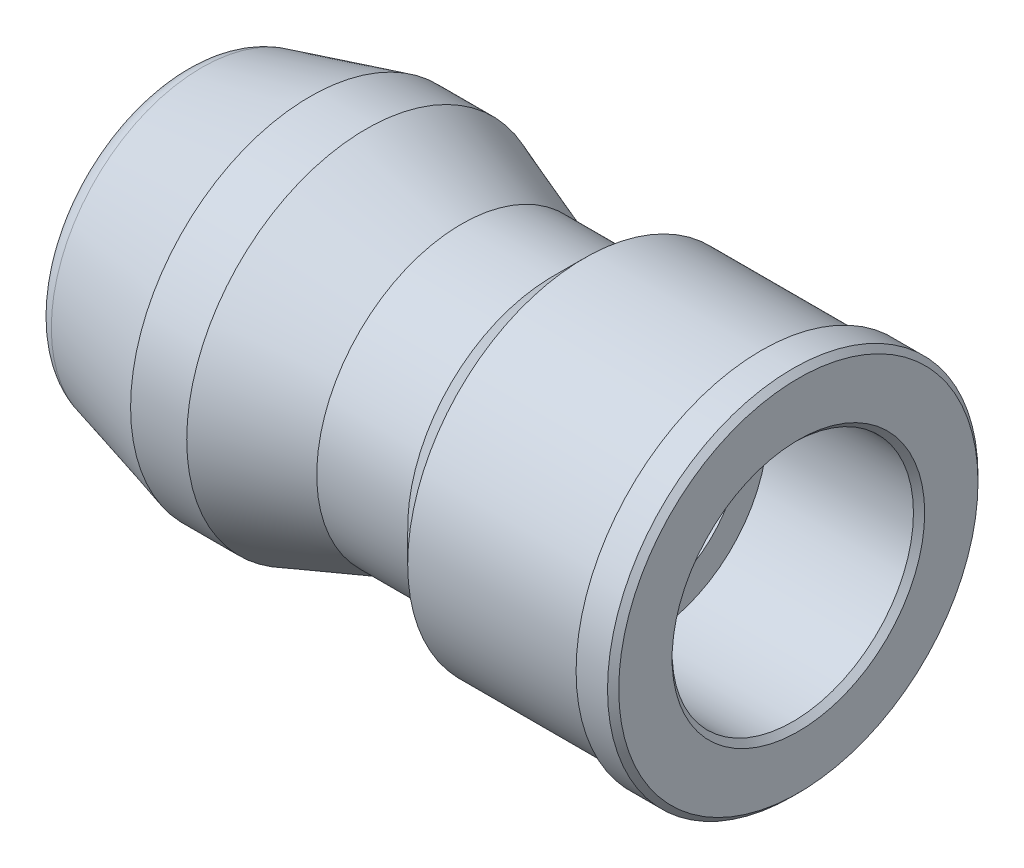
SolidWorks part; units mm, degrees
ref_plane "Front Plane" through (0, 0, 0) normal (0, 0, 1) x (1, 0, 0)
ref_plane "Top Plane" through (0, 0, 0) normal (0, 1, 0) x (1, 0, 0)
ref_plane "Right Plane" through (0, 0, 0) normal (1, 0, 0) x (0, 0, -1)
sketch "Sketch1" plane through (0, 0, 0) normal (0, 0, 1) x (1, 0, 0)
  line L0 (5.8896, 0) -> (0, 0)
  line L1 (0, 0) -> (0, 2.58)
  line L2 (0, 2.58) -> (2.3, 3.1963)
  line L3 (2.3, 3.1963) -> (3.3, 3.1963)
  line L4 (3.3, 3.1963) -> (5, 2.58)
  line L5 (5, 2.58) -> (6.62, 2.58)
  line L6 (6.62, 2.58) -> (7.19, 3.15)
  line L7 (7.19, 3.15) -> (10.34, 3.15)
  line L8 (10.34, 3.3) -> (11, 3.3)
  line L9 (11, 3.3) -> (11, 2.15)
  line L10 (11, 2.15) -> (8.3, 2.15)
  line L11 (8.3, 2.15) -> (8.3, 0)
  line L12 (8.3, 0) -> (5.8896, 0)
  line L13 (10.34, 3.15) -> (10.34, 3.3)
  point P14 (0, 0)
  dimension "D1" = 8.3
  dimension "D2" = 2.58
  dimension "D3" = 105
  dimension "D4" = 2.3
  dimension "D5" = 1.7
  dimension "D6" = 135
  dimension "D7" = 1
  dimension "D8" = 1.62
  dimension "D9" = 3.15
  dimension "D10" = 1.15
  dimension "D11" = 2.15
  dimension "D12" = 2.7
  dimension "D13" = 1
revolve "Revolve1" add sketch "Sketch1" angle 360 about L0
sketch "Sketch4" plane through (0, 0, 0) normal (-1, 0, 0) x (0, 0, 1)
  point P0 (0, 0)
hole_wizard "M4 Tapped Hole1" positions "Sketch4" profile "Sketch3" tap size "M4" standard "ISO" end condition through all
sketch "Sketch3" plane through (0, 0, 0) normal (0, 1, 0) x (0, 0, 1)
  line L0 (0, 0) -> (0, 11)
  line L1 (0, 11) -> (1.65, 11)
  line L2 (1.65, 11) -> (1.65, 0.9053)
  line L3 (1.65, 0.9053) -> (2.025, 0)
  line L5 (2.025, 0) -> (0, 0)
  line L6 (-1.65, 0.9053) -> (-2.025, 0) construction
  line L11 (0, -6.35) -> (0, 107.95) construction
  dimension "Thru Tap Drill Dia." = 3.3
  dimension "Thru Tap Drill Depth" = 11
  dimension "Near C'Sink Dia." = 4.05
  dimension "Near C'Sink Angle" = 45
cosmetic thread "Hole Thread1" parameters "D2"=4
fillet "Fillet1" radius 0.5 1 edges at (0, 0, -2.58)
chamfer "Chamfer1" distance 0.1 angle 45 3 edges at (11, 0, -2.15) (11, 0, -3.3) (10.34, 0, -3.15)
